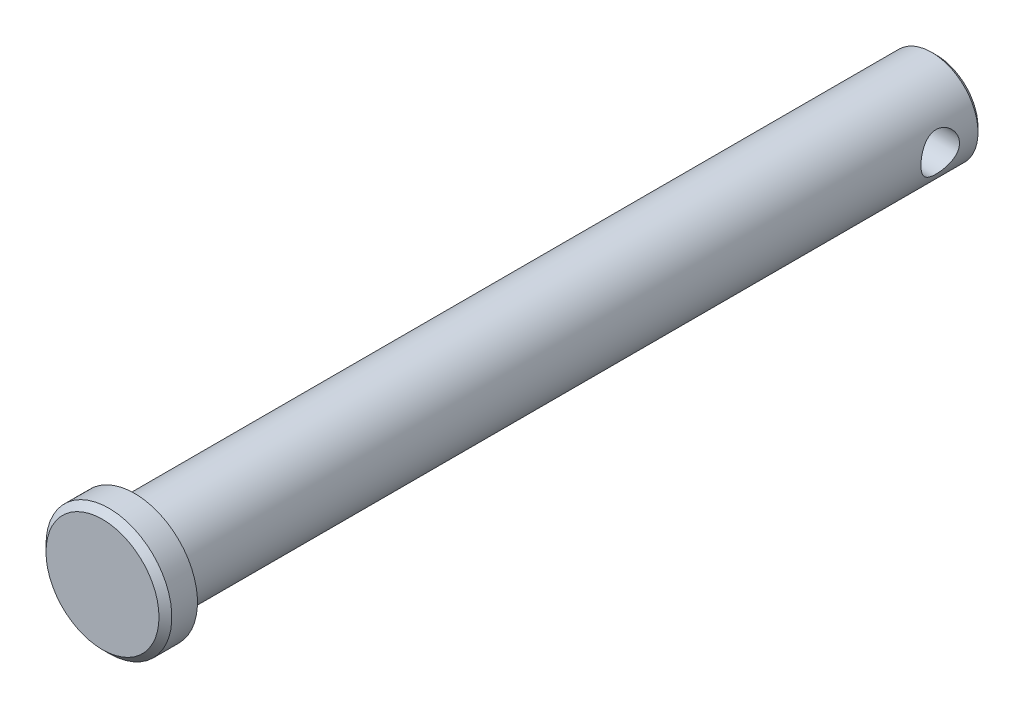
SolidWorks part; units mm, degrees
material "Plain Carbon Steel"
ref_plane "Front" through (0, 0, 0) normal (0, 0, 1) x (1, 0, 0)
ref_plane "Top" through (0, 0, 0) normal (0, 1, 0) x (1, 0, 0)
ref_plane "Right" through (0, 0, 0) normal (1, 0, 0) x (0, 0, -1)
sketch "Sketch1" plane through (0, 0, 0) normal (0, 0, 1) x (1, 0, 0)
  circle A0 centre (0, 0) radius 4.7625
  point P3 (0, 4.7625)
  point P4 (0, -4.7625)
  dimension "dia" = 9.525
extrude "Extrude1" add sketch "Sketch1" along normal mid plane 82.55
sketch "Sketch2" plane through (0, 0, 41.275) normal (0, 0, 1) x (1, 0, 0)
  circle A0 centre (0, 0) radius 6.477
  dimension "head dia" = 12.954
extrude "Extrude2" add sketch "Sketch2" along normal blind 3.302
chamfer "Chamfer1" distance 0.6604 angle 45 1 edges at (6.477, 0, 44.577)
sketch "Sketch3" plane through (0, 0, 0) normal (1, 0, 0) x (0, 0, -1)
  line L0 (-41.275, -4.7625) -> (-41.275, 4.7625) construction
  circle A0 centre (36.9094, 0) radius 1.9844
  point P2 (34.925, 0)
  dimension "hole dia" = 3.9688
  dimension "useable Lg" = 76.2
extrude "Extrude3" cut sketch "Sketch3" against normal through all and the other way through all
chamfer "Chamfer2" distance 0.4763 angle 45 1 edges at (4.7625, 0, -41.275)
ref_plane "Plane1" through (0, 0, -36.9094) normal (0, 0, 1) x (1, 0, 0)
sketch "Sketch8" plane through (0, 0, 0) normal (1, 0, 0) x (0, 0, -1)
  line L0 (-44.577, 5.8166) -> (-44.577, -5.8166) construction
  line L1 (-43.9166, -6.477) -> (-41.275, -6.477) construction
  line L2 (41.275, -4.2863) -> (41.275, 4.2863) construction
  point P0 (-44.577, 6.477)
  point P1 (-41.275, 6.477)
  point P5 (41.275, 4.7625)
  point P8 (-44.577, -6.477)
  point P9 (41.275, -4.7625)
equation "\"D1@Chamfer1\" = \"head ht@Extrude2\" * .2"
equation "\"D1@Chamfer2\" = \"dia@Sketch1\" * .05"
